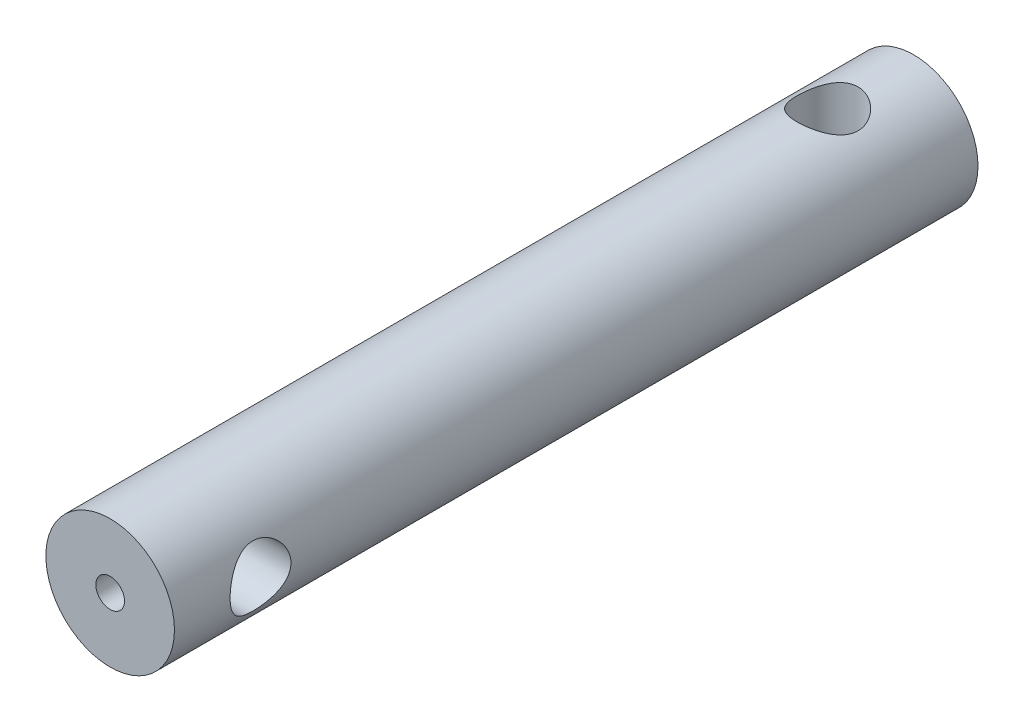
SolidWorks part; units mm, degrees
ref_plane "Front" through (0, 0, 0) normal (0, 0, 1) x (1, 0, 0)
ref_plane "Top" through (0, 0, 0) normal (0, 1, 0) x (1, 0, 0)
ref_plane "Right" through (0, 0, 0) normal (1, 0, 0) x (0, 0, -1)
sketch "Sketch1" plane through (0, 0, 0) normal (0, 0, 1) x (1, 0, 0)
  circle A0 centre (0, 0) radius 7.112
  circle A1 centre (0, 0) radius 1.5875
  dimension "D1" = 14.224
  dimension "D2" = 3.175
extrude "Boss-Extrude1" add sketch "Sketch1" along normal blind 88.9
sketch "Sketch7" plane through (0, 0, 0) normal (0, 1, 0) x (1, 0, 0)
  line L1 (1.5875, 0) -> (-1.5875, 0) construction
  line L3 (7.112, 0) -> (-7.112, 0) construction
  circle A0 centre (0, -9.525) radius 3.3655
  dimension "D1" = 9.525
  dimension "D2" = 9.525
  dimension "D3" = 9.525
  dimension "D4" = 9.525
extrude "Cut-Extrude2" cut sketch "Sketch7" against normal through all both and the other way through all
sketch "Sketch8" plane through (0, 0, 0) normal (1, 0, 0) x (0, 0, -1)
  circle A0 centre (-79.375, 0) radius 3.3655
extrude "Cut-Extrude3" cut sketch "Sketch8" against normal through all both and the other way through all
